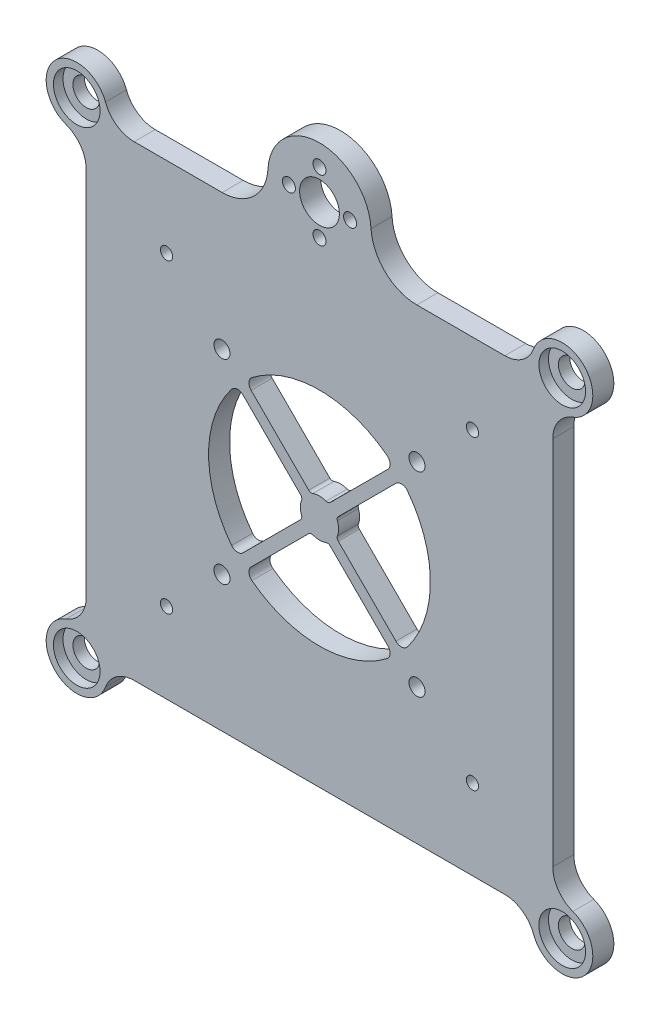
SolidWorks part; units mm, degrees
ref_plane "前视基准面" through (0, 0, 0) normal (0, 0, 1) x (1, 0, 0)
ref_plane "上视基准面" through (0, 0, 0) normal (0, 1, 0) x (1, 0, 0)
ref_plane "右视基准面" through (0, 0, 0) normal (1, 0, 0) x (0, 0, -1)
sketch "草图1" plane through (0, 0, 0) normal (0, 0, 1) x (1, 0, 0)
  line L0 (-48.4591, -61) -> (48.4591, -61)
  line L1 (61, -48.4591) -> (61, 48.4591)
  line L2 (48.4591, 61) -> (25.4558, 61)
  line L3 (-61, 48.4591) -> (-61, -48.4591)
  line L4 (-48.4591, 61) -> (-25.4558, 61)
  arc A0 (-55.967, 66.2374) -> (-66.2374, 55.967) centre (-63.4749, 63.4749) ccw
  arc A1 (-55.967, 66.2374) -> (-48.4591, 61) centre (-48.4591, 69) ccw
  arc A2 (-61, 48.4591) -> (-66.2374, 55.967) centre (-69, 48.4591) ccw
  arc A3 (66.2374, 55.967) -> (55.967, 66.2374) centre (63.4749, 63.4749) ccw
  arc A4 (66.2374, 55.967) -> (61, 48.4591) centre (69, 48.4591) ccw
  arc A5 (48.4591, 61) -> (55.967, 66.2374) centre (48.4591, 69) ccw
  arc A6 (55.967, -66.2374) -> (66.2374, -55.967) centre (63.4749, -63.4749) ccw
  arc A7 (61, -48.4591) -> (66.2374, -55.967) centre (69, -48.4591) ccw
  arc A8 (55.967, -66.2374) -> (48.4591, -61) centre (48.4591, -69) ccw
  arc A9 (-66.2374, -55.967) -> (-55.967, -66.2374) centre (-63.4749, -63.4749) ccw
  arc A10 (-48.4591, -61) -> (-55.967, -66.2374) centre (-48.4591, -69) ccw
  arc A11 (-66.2374, -55.967) -> (-61, -48.4591) centre (-69, -48.4591) ccw
  arc A12 (13.4766, 72.2941) -> (-13.4766, 72.2941) centre (0, 71.5) ccw
  arc A13 (-25.4558, 61) -> (-13.4766, 72.2941) centre (-25.4558, 73) ccw
  arc A14 (13.4766, 72.2941) -> (25.4558, 61) centre (25.4558, 73) ccw
extrude "凸台-拉伸1" add sketch "草图1" against normal blind 5.5
sketch "草图2" plane through (0, 0, 0) normal (0, 0, 1) x (1, 0, 0)
  circle A0 centre (-63.4749, 63.4749) radius 6.1
  circle A1 centre (63.4749, 63.4749) radius 6.1
  circle A2 centre (63.4749, -63.4749) radius 6.1
  circle A3 centre (-63.4749, -63.4749) radius 6.1
extrude "切除-拉伸1" cut sketch "草图2" against normal blind 2.5
sketch "草图3" plane through (0, 0, -2.5) normal (0, 0, 1) x (1, 0, 0)
  circle A0 centre (-63.4749, 63.4749) radius 3.5
  circle A1 centre (63.4749, 63.4749) radius 3.5
  circle A2 centre (-63.4749, -63.4749) radius 3.5
  circle A3 centre (63.4749, -63.4749) radius 3.5
extrude "切除-拉伸2" cut sketch "草图3" against normal blind 3
sketch "草图4" plane through (0, 0, 0) normal (0, 0, 1) x (1, 0, 0)
  circle A0 centre (8, 71.5) radius 1.7
  circle A1 centre (0, 79.5) radius 1.7
  circle A2 centre (-8, 71.5) radius 1.7
  circle A3 centre (0, 63.5) radius 1.7
extrude "切除-拉伸3" cut sketch "草图4" against normal blind 5.5
sketch "草图5" plane through (0, 0, 0) normal (0, 0, 1) x (1, 0, 0)
  circle A0 centre (0, 71.5) radius 5.2
extrude "切除-拉伸4" cut sketch "草图5" against normal blind 5.5
sketch "草图6" plane through (0, 0, 0) normal (0, 0, 1) x (1, 0, 0)
  circle A0 centre (-40, 40) radius 1.6
  circle A1 centre (40, 40) radius 1.6
  circle A2 centre (40, -40) radius 1.6
  circle A3 centre (-40, -40) radius 1.6
  circle A4 centre (-25.5, 25.5) radius 2.1
  circle A5 centre (25.5, 25.5) radius 2.1
  circle A6 centre (25.5, -25.5) radius 2.1
  circle A7 centre (-25.5, -25.5) radius 2.1
extrude "切除-拉伸5" cut sketch "草图6" against normal blind 5.5
sketch "草图7" plane through (0, 0, 0) normal (0, 0, 1) x (1, 0, 0)
  circle A0 centre (0, 0) radius 29
sketch "草图8" plane through (0, 0, 0) normal (0, 0, 1) x (1, 0, 0)
  line L0 (4.9175, 2.7962) -> (19.9915, 17.8701)
  line L1 (2.7962, 4.9175) -> (17.8701, 19.9915)
  line L2 (-4.9175, 2.7962) -> (-19.9915, 17.8701)
  line L3 (-2.7962, 4.9175) -> (-17.8701, 19.9915)
  line L4 (4.9175, -2.7962) -> (19.9915, -17.8701)
  line L5 (2.7962, -4.9175) -> (17.8701, -19.9915)
  line L6 (-4.9175, -2.7962) -> (-19.9915, -17.8701)
  line L7 (-2.7962, -4.9175) -> (-17.8701, -19.9915)
  arc A0 (-17.6749, -22.9913) -> (17.6749, -22.9913) centre (0, 0) ccw
  arc A1 (17.6749, -22.9913) -> (17.8701, -19.9915) centre (16.4559, -21.4057) ccw
  arc A2 (-17.8701, -19.9915) -> (-17.6749, -22.9913) centre (-16.4559, -21.4057) ccw
  arc A3 (22.9913, -17.6749) -> (22.9913, 17.6749) centre (0, 0) ccw
  arc A4 (22.9913, 17.6749) -> (19.9915, 17.8701) centre (21.4057, 16.4559) ccw
  arc A5 (19.9915, -17.8701) -> (22.9913, -17.6749) centre (21.4057, -16.4559) ccw
  arc A6 (17.6749, 22.9913) -> (-17.6749, 22.9913) centre (0, 0) ccw
  arc A7 (-17.6749, 22.9913) -> (-17.8701, 19.9915) centre (-16.4559, 21.4057) ccw
  arc A8 (17.8701, 19.9915) -> (17.6749, 22.9913) centre (16.4559, 21.4057) ccw
  arc A9 (-22.9913, 17.6749) -> (-22.9913, -17.6749) centre (0, 0) ccw
  arc A10 (-22.9913, -17.6749) -> (-19.9915, -17.8701) centre (-21.4057, -16.4559) ccw
  arc A11 (-19.9915, 17.8701) -> (-22.9913, 17.6749) centre (-21.4057, 16.4559) ccw
  arc A12 (-4.6871, 1.7409) -> (-4.6871, -1.7409) centre (0, 0) ccw
  arc A13 (-4.6871, 1.7409) -> (-4.9175, 2.7962) centre (-5.6246, 2.089) ccw
  arc A14 (-4.9175, -2.7962) -> (-4.6871, -1.7409) centre (-5.6246, -2.089) ccw
  arc A15 (-1.7409, -4.6871) -> (1.7409, -4.6871) centre (0, 0) ccw
  arc A16 (-1.7409, -4.6871) -> (-2.7962, -4.9175) centre (-2.089, -5.6246) ccw
  arc A17 (2.7962, -4.9175) -> (1.7409, -4.6871) centre (2.089, -5.6246) ccw
  arc A18 (4.6871, -1.7409) -> (4.6871, 1.7409) centre (0, 0) ccw
  arc A19 (4.6871, -1.7409) -> (4.9175, -2.7962) centre (5.6246, -2.089) ccw
  arc A20 (4.9175, 2.7962) -> (4.6871, 1.7409) centre (5.6246, 2.089) ccw
  arc A21 (1.7409, 4.6871) -> (-1.7409, 4.6871) centre (0, 0) ccw
  arc A22 (1.7409, 4.6871) -> (2.7962, 4.9175) centre (2.089, 5.6246) ccw
  arc A23 (-2.7962, 4.9175) -> (-1.7409, 4.6871) centre (-2.089, 5.6246) ccw
extrude "切除-拉伸6" cut sketch "草图8" against normal blind 10
